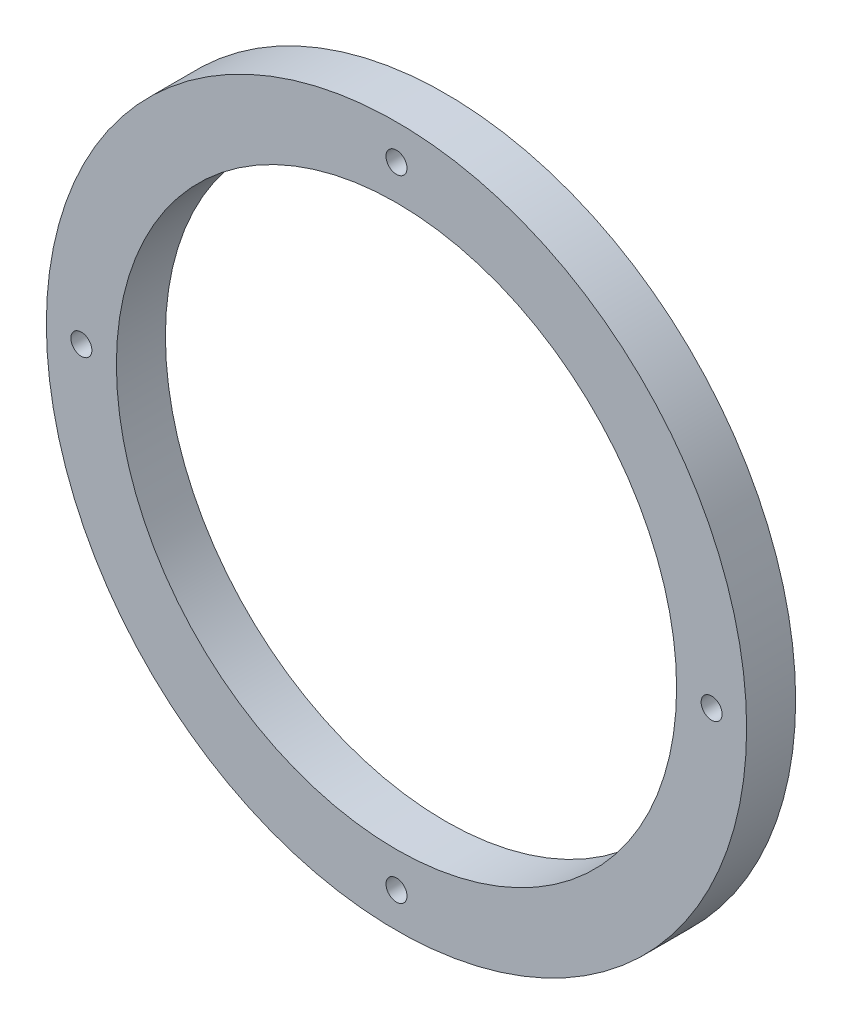
SolidWorks part; units mm, degrees
ref_plane "Front Plane" through (0, 0, 0) normal (0, 0, 1) x (1, 0, 0)
ref_plane "Top Plane" through (0, 0, 0) normal (0, 1, 0) x (1, 0, 0)
ref_plane "Right Plane" through (0, 0, 0) normal (1, 0, 0) x (0, 0, -1)
sketch "Sketch1" plane through (0, 0, 0) normal (0, 0, 1) x (1, 0, 0)
  circle A0 centre (0, 0) radius 40
  circle A1 centre (0, 0) radius 50
  dimension "D1" = 80
  dimension "D2" = 100
extrude "Boss-Extrude1" add sketch "Sketch1" along normal blind 7
sketch "Sketch2" plane through (0, 0, 7) normal (0, 0, 1) x (1, 0, 0)
  line L0 (0, 18.0512) -> (0, 79.0405) construction
  line L1 (-2.5198, 0) -> (97.6434, 0) construction
  line L2 (-45, 0) -> (0, 0) construction
  line L3 (0, 0) -> (45, 0) construction
  line L4 (0, 45) -> (0, 0) construction
  line L5 (0, -45) -> (0, 0) construction
  circle A0 centre (0, 45) radius 1.5
  circle A1 centre (0, -45) radius 1.5
  circle A2 centre (-45, 0) radius 1.5
  circle A3 centre (45, 0) radius 1.5
  point P4 (0, 0)
  dimension "D1" = 3
  dimension "D2" = 45
extrude "Cut-Extrude1" cut sketch "Sketch2" against normal through all
